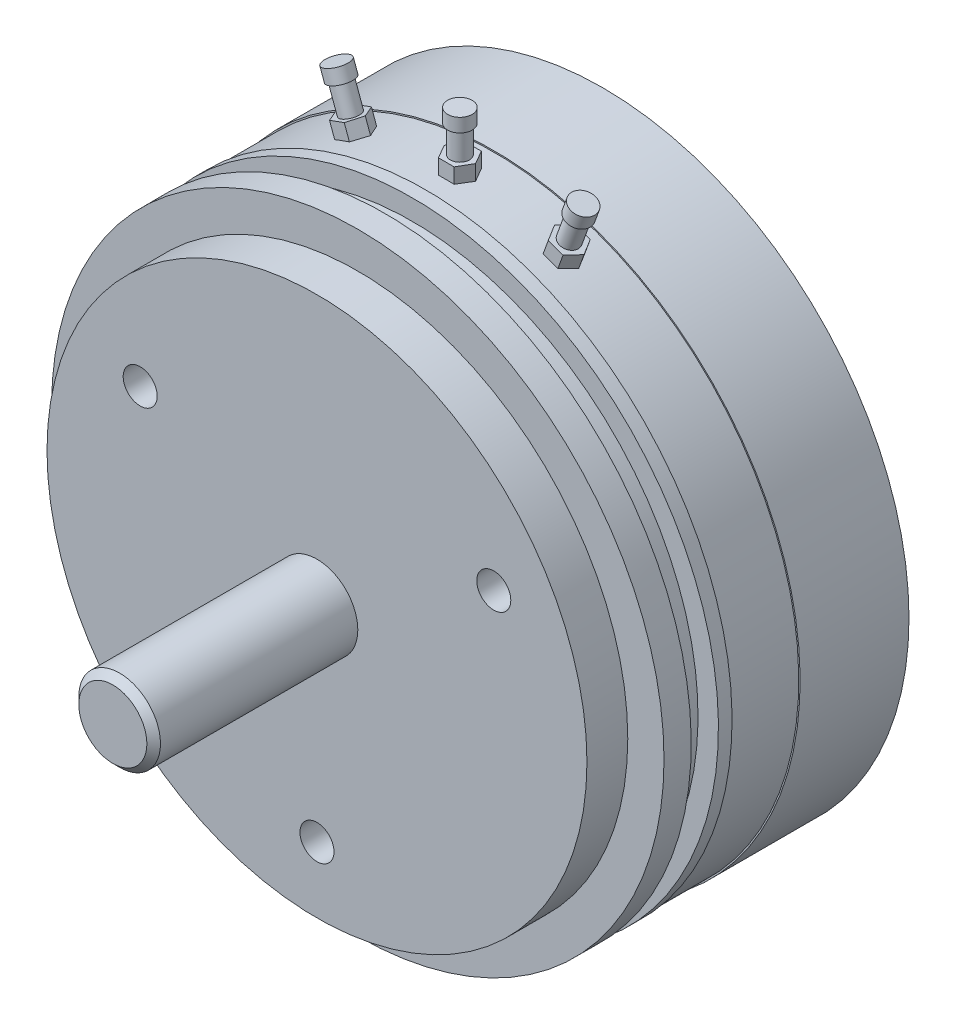
SolidWorks part; units mm, degrees
ref_plane "Front Plane" through (0, 0, 0) normal (0, 0, 1) x (1, 0, 0)
ref_plane "Top Plane" through (0, 0, 0) normal (0, 1, 0) x (1, 0, 0)
ref_plane "Right Plane" through (0, 0, 0) normal (1, 0, 0) x (0, 0, -1)
sketch "Sketch1" plane through (0, 0, 0) normal (0, 0, 1) x (1, 0, 0)
  circle A0 centre (0, 0) radius 22.5
  dimension "D1" = 45
extrude "Boss-Extrude1" add sketch "Sketch1" along normal blind 18
sketch "Sketch2" plane through (0, 0, 0) normal (1, 0, 0) x (0, 0, -1)
  line L0 (0, 22.5) -> (-18, 22.5) construction
  line L1 (-16, 22.5) -> (-14, 22.5)
  line L2 (-16, 22.5) -> (-16, 21)
  line L3 (-16, 21) -> (-14, 21)
  line L4 (-14, 22.5) -> (-14, 21)
  line L5 (-18, 22.5) -> (-18, -22.5) construction
  line L6 (-18, 0) -> (0, 0) construction
  line L8 (-13, 22.5) -> (-8, 22.5)
  line L9 (-13, 22.5) -> (-13, 22.4)
  line L10 (-13, 22.4) -> (-8, 22.4)
  line L11 (-8, 22.5) -> (-8, 22.4)
  dimension "D1" = 21
  dimension "D2" = 2
  dimension "D3" = 2
  dimension "D4" = 1
  dimension "D5" = 5
  dimension "D6" = 0.1
revolve "Cut-Revolve1" cut sketch "Sketch2" angle 360 about L6
sketch "Sketch3" plane through (0, 0, 18) normal (0, 0, 1) x (1, 0, 0)
  circle A0 centre (0, 0) radius 19.8375
  dimension "D1" = 39.675
extrude "Boss-Extrude2" add sketch "Sketch3" along normal blind 3
sketch "Sketch4" plane through (0, 0, 21) normal (0, 0, 1) x (1, 0, 0)
  circle A0 centre (0, 0) radius 3
  dimension "D1" = 6
extrude "Boss-Extrude3" add sketch "Sketch4" along normal blind 15
sketch "Sketch5" plane through (0, 0, 0) normal (0, 0, -1) x (-1, 0, 0)
  circle A0 centre (0, 0) radius 3
  dimension "D1" = 6
extrude "Boss-Extrude4" add sketch "Sketch5" along normal blind 10
chamfer "Chamfer1" distance 0.5 angle 45 2 edges at (-3, 0, -10) (3, 0, 36)
hole_wizard "M3x0.5 Tapped Hole1" positions "Sketch8" profile "Sketch9" tap size "M3x0.5" standard "ANSI Metric"
sketch "Sketch8" plane through (0, 0, 21) normal (0, 0, 1) x (1, 0, 0)
  line L0 (-12.9904, 7.5) -> (0, 0) construction
  line L1 (0, 0) -> (0, -15) construction
  line L3 (12.9904, 7.5) -> (0, 0) construction
  circle A0 centre (0, 0) radius 15 construction
  point P5 (0, -15)
  point P7 (-12.9904, 7.5)
  point P9 (12.9904, 7.5)
  dimension "D2" = 30
  dimension "D1" = 120
  dimension "D3" = 120
sketch "Sketch9" plane through (12.9904, 7.5, 21) normal (1, 0, 0) x (0, -1, 0)
  line L0 (0, 0) -> (0, 4)
  line L1 (0, 4) -> (1.25, 4)
  line L2 (1.25, 4) -> (1.25, 0)
  line L5 (1.25, 0) -> (0, 0)
  line L10 (0, 4) -> (-1.25, 4) construction
  line L11 (0, -6.35) -> (0, 107.95) construction
  dimension "Tap Drill Dia." = 2.5
  dimension "Tap Drill Depth" = 4
  dimension "Drill Angle" = 180
cosmetic thread "Hole Thread1" parameters "D1"=4, "D2"=3
cosmetic thread "Hole Thread2" parameters "D1"=4, "D2"=3
cosmetic thread "Hole Thread3" parameters "D1"=4, "D2"=3
sketch "Sketch10" plane through (0, 0, 0) normal (0, 1, 0) x (1, 0, 0)
  line L1 (1.1547, -10.5) -> (0.5774, -9.5)
  line L2 (0.5774, -9.5) -> (-0.5774, -9.5)
  line L3 (-0.5774, -9.5) -> (-1.1547, -10.5)
  line L4 (-1.1547, -10.5) -> (-0.5774, -11.5)
  line L5 (-0.5774, -11.5) -> (0.5774, -11.5)
  line L6 (0.5774, -11.5) -> (1.1547, -10.5)
  circle A0 centre (0, -10.5) radius 1 construction
  dimension "D1" = 2
  dimension "D2" = 10.5
extrude "Boss-Extrude5" add sketch "Sketch10" along normal blind 23.5
sketch "Sketch11" plane through (0, 23.5, 0) normal (0, 1, 0) x (1, 0, 0)
  circle A0 centre (0, -10.5) radius 0.7
  dimension "D2" = 1.4
  dimension "D1" = 10.5
extrude "Boss-Extrude6" add sketch "Sketch11" along normal blind 2
sketch "Sketch12" plane through (0, 25.5, 0) normal (0, 1, 0) x (1, 0, 0)
  circle A0 centre (0, -10.5) radius 0.9
  dimension "D1" = 1.8
extrude "Boss-Extrude7" add sketch "Sketch12" along normal blind 1
pattern_circular "CirPattern1" count 2 every 20 about axis through (0, 0, 0) along (0, 0, 1) of "Boss-Extrude5", "Boss-Extrude6", "Boss-Extrude7"
